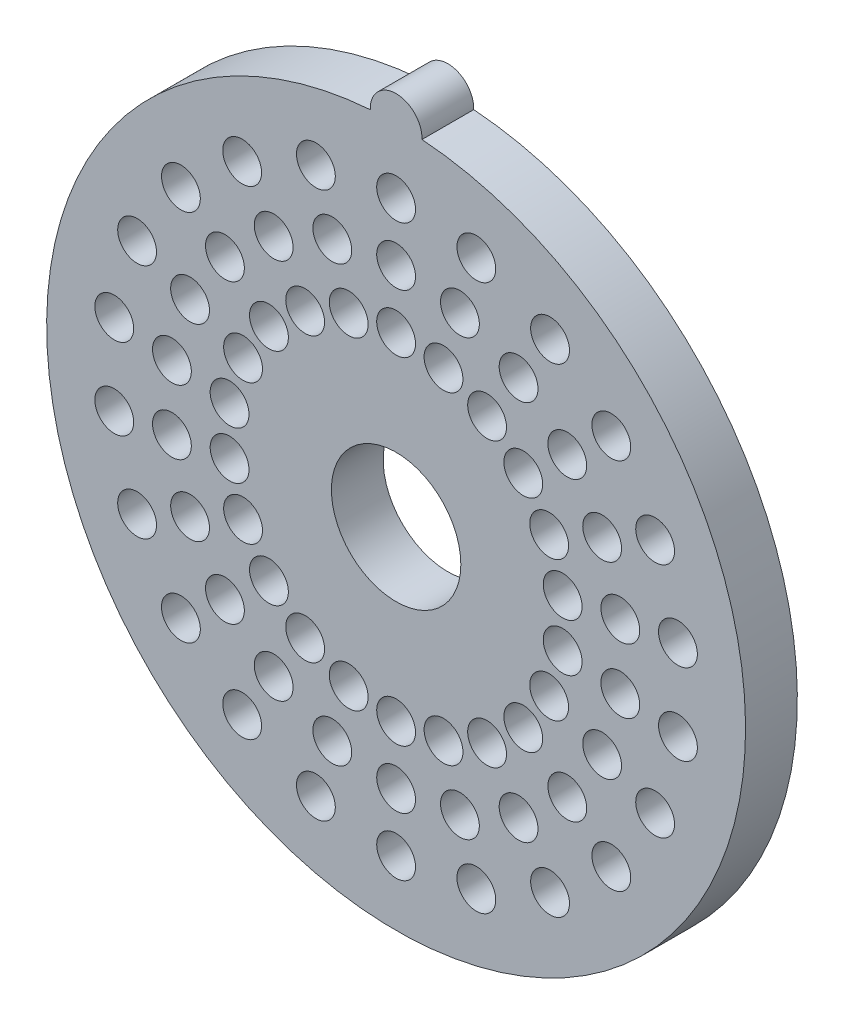
SolidWorks part; units mm, degrees
ref_plane "Front Plane" through (0, 0, 0) normal (0, 0, 1) x (1, 0, 0)
ref_plane "Top Plane" through (0, 0, 0) normal (0, 1, 0) x (1, 0, 0)
ref_plane "Right Plane" through (0, 0, 0) normal (1, 0, 0) x (0, 0, -1)
sketch "Sketch1" plane through (0, 0, 0) normal (0, 0, 1) x (1, 0, 0)
  line L0 (-51.4104, 0) -> (44.7615, 0) construction
  line L1 (0, 36.6397) -> (0, -36.2857) construction
  arc A0 (-1.9986, 26.9259) -> (1.9986, 26.9259) centre (0, 0) ccw
  circle A1 centre (0, 0) radius 5
  circle A2 centre (0, 0) radius 22 construction
  circle A3 centre (0, 0) radius 17.5 construction
  circle A4 centre (0, 0) radius 13 construction
  arc A5 (1.9986, 26.9259) -> (-1.9986, 26.9259) centre (0, 27) ccw
  dimension "D1" = 54
  dimension "D2" = 10
  dimension "D3" = 44
  dimension "D4" = 35
  dimension "D5" = 26
  dimension "D6" = 4
extrude "Boss-Extrude1" add sketch "Sketch1" along normal blind 4
sketch "Sketch2" plane through (0, 0, 4) normal (0, 0, 1) x (1, 0, 0)
  line L0 (0, 36.6397) -> (0, -36.2857) construction
  circle A0 centre (0, 13) radius 1.5
  circle A1 centre (0, 0) radius 13 construction
  circle A2 centre (0, 17.5) radius 1.5
  circle A3 centre (0, 0) radius 17.5 construction
  circle A4 centre (0, 22) radius 1.5
  circle A5 centre (0, 0) radius 22 construction
  dimension "D1" = 3
extrude "Cut-Extrude1" cut sketch "Sketch2" against normal through all
pattern_circular "CirPattern1" count 22 over 360 about axis through (0, 0, 0) along (0, 0, 1) of "Cut-Extrude1"
